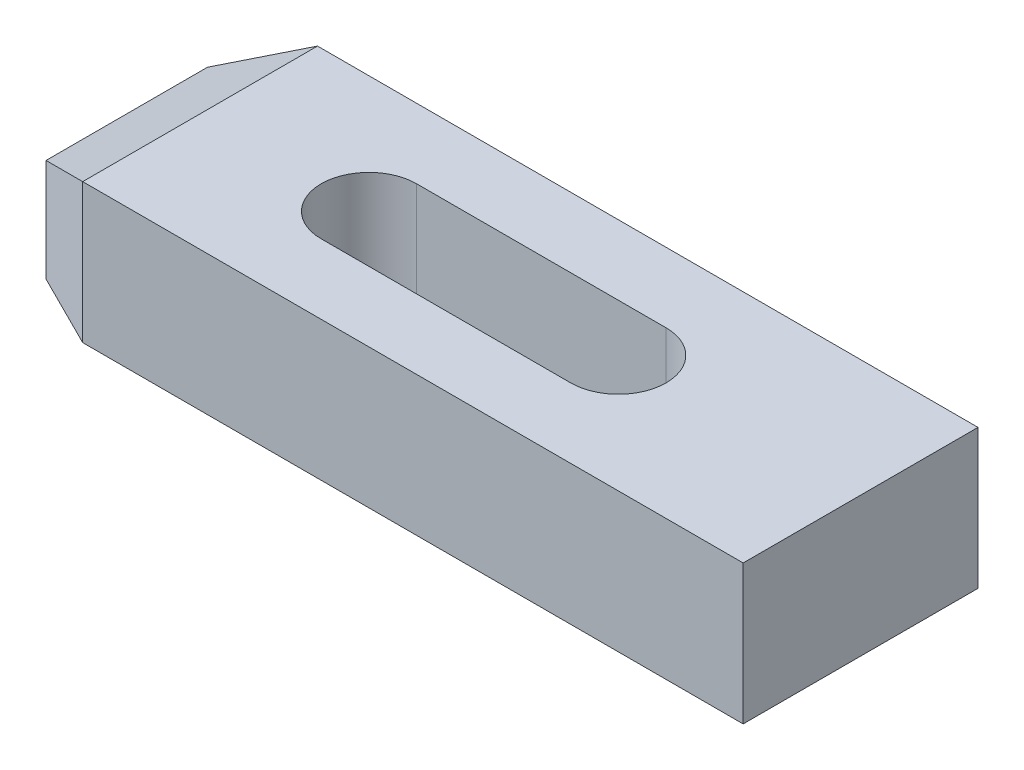
SolidWorks part; units mm, degrees
ref_plane "Front Plane" through (0, 0, 0) normal (0, 0, 1) x (1, 0, 0)
ref_plane "Top Plane" through (0, 0, 0) normal (0, 1, 0) x (1, 0, 0)
ref_plane "Right Plane" through (0, 0, 0) normal (1, 0, 0) x (0, 0, -1)
sketch "Sketch1" plane through (0, 0, 0) normal (0, 1, 0) x (1, 0, 0)
  line L0 (-17, 0) -> (17, 0) construction
  line L1 (-40, -16) -> (50, -16)
  line L2 (-50, -11) -> (-50, 11)
  line L3 (-40, 16) -> (50, 16)
  line L4 (50, -16) -> (50, 16)
  line L5 (-50, -16) -> (50, 16) construction
  line L6 (-50, 16) -> (50, -16) construction
  line L7 (-17, 6.5) -> (17, 6.5)
  line L8 (-17, -6.5) -> (17, -6.5)
  line L9 (-40, 16) -> (-40, -16) construction
  line L10 (-40, -16) -> (-50, -11)
  line L11 (-40, 16) -> (-50, 11)
  line L12 (-40, 16) -> (-50, 16) construction
  line L13 (-50, 16) -> (-50, 11) construction
  line L14 (-50, -11) -> (-50, -16) construction
  line L15 (-50, -16) -> (-40, -16) construction
  arc A0 (-17, 6.5) -> (-17, -6.5) centre (-17, 0) ccw
  arc A1 (17, -6.5) -> (17, 6.5) centre (17, 0) ccw
  point P0 (0, 0)
  point P8 (0, 0)
  dimension "D1" = 100
  dimension "D2" = 32
  dimension "D3" = 13
  dimension "D4" = 34
  dimension "D5" = 10
  dimension "D6" = 5
extrude "Boss-Extrude1" add sketch "Sketch1" along normal blind 19
sketch "Sketch2" plane through (0, 0, 16) normal (0, 0, 1) x (1, 0, 0)
  line L0 (-50, 19) -> (-40, 19)
  line L1 (-40, 19) -> (50, 19) construction
  line L2 (-40, 19) -> (-50, 14)
  line L3 (-50, 19) -> (-50, 0) construction
  line L4 (-50, 14) -> (-50, 19)
  dimension "D1" = 10
  dimension "D2" = 5
extrude "Cut-Extrude1" cut sketch "Sketch2" against normal through all
